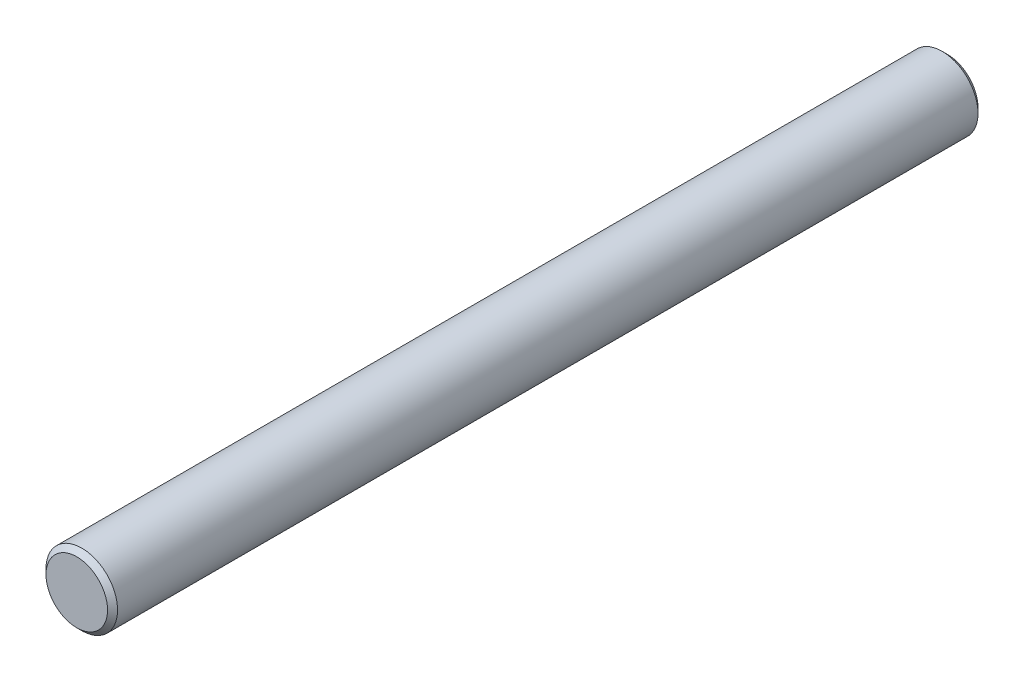
SolidWorks part; units mm, degrees
ref_plane "Front Plane" through (0, 0, 0) normal (0, 0, 1) x (1, 0, 0)
ref_plane "Top Plane" through (0, 0, 0) normal (0, 1, 0) x (1, 0, 0)
ref_plane "Right Plane" through (0, 0, 0) normal (1, 0, 0) x (0, 0, -1)
sketch "Sketch1" plane through (0, 0, 0) normal (0, 0, 1) x (1, 0, 0)
  line L0 (-3.9688, 0) -> (3.9688, 0) construction
  line L5 (0, 3.9688) -> (0, -3.9688) construction
  circle A1 centre (0, 0) radius 3.9688
  point P7 (-3.9688, 0)
  point P8 (3.9688, 0)
  point P12 (0, -3.9688)
  point P13 (0, 3.9688)
  dimension "Diameter" = 7.9375
sketch "Sketch2" plane through (0, 0, 0) normal (1, 0, 0) x (0, 0, -1)
  line L0 (-40.3225, -3.9688) -> (-40.3225, 3.9687) construction
  line L1 (48.26, -3.9688) -> (-48.26, -3.9688)
  line L2 (48.26, -3.9688) -> (48.26, 3.9688)
  line L3 (48.26, 3.9688) -> (-48.26, 3.9688)
  line L4 (-48.26, -3.9688) -> (-48.26, 3.9688)
  line L5 (48.26, -3.9688) -> (-48.26, 3.9688) construction
  line L6 (48.26, 3.9688) -> (-48.26, -3.9688) construction
  line L7 (40.3225, -3.9688) -> (40.3225, 3.9687) construction
  line L8 (-48.26, 3.4131) -> (-47.7044, 3.9687) construction
  point P0 (0, 0)
  point P8 (-48.26, 3.9688)
  point P9 (48.26, 3.9688)
  point P14 (-40.3225, 3.9687)
  point P15 (-40.3225, -3.9688)
  point P16 (40.3225, 3.9687)
  point P17 (40.3225, -3.9688)
  point P25 (0, -3.9688)
  dimension "Length" = 96.52
  dimension "D1" = 7.9375
  dimension "D2" = 7.9375
  dimension "Chamfer Typ," = 45
  dimension "D4" = 0.5556
sketch "Sketch3" plane through (0, 0, 0) normal (0, 0, 1) x (1, 0, 0)
  circle A0 centre (0, 0) radius 3.9688 construction
  circle A1 centre (0, 0) radius 3.9688
extrude "Boss-Extrude1" add sketch "Sketch3" along normal up to vertex (48.26 mm away) and the other way up to vertex (48.26 mm away) up to point (0, 3.9688, 48.26) other way up to point (0, 3.9688, -48.26)
chamfer "Chamfer1" distance 0.5556 angle 45 2 edges at (3.9688, 0, -48.26) (3.9688, 0, 48.26)
equation "\"D1@Sketch2\"=\"Diameter@Sketch1\""
equation "\"D2@Sketch2\"=\"Diameter@Sketch1\""
equation "\"D1@Chamfer1\"=\"Diameter@Sketch1\"*.07"
equation "\"D4@Sketch2\"=\"Diameter@Sketch1\"*.07"
equation "\"D2@Chamfer1\"=\"Chamfer Typ,@Sketch2\""
